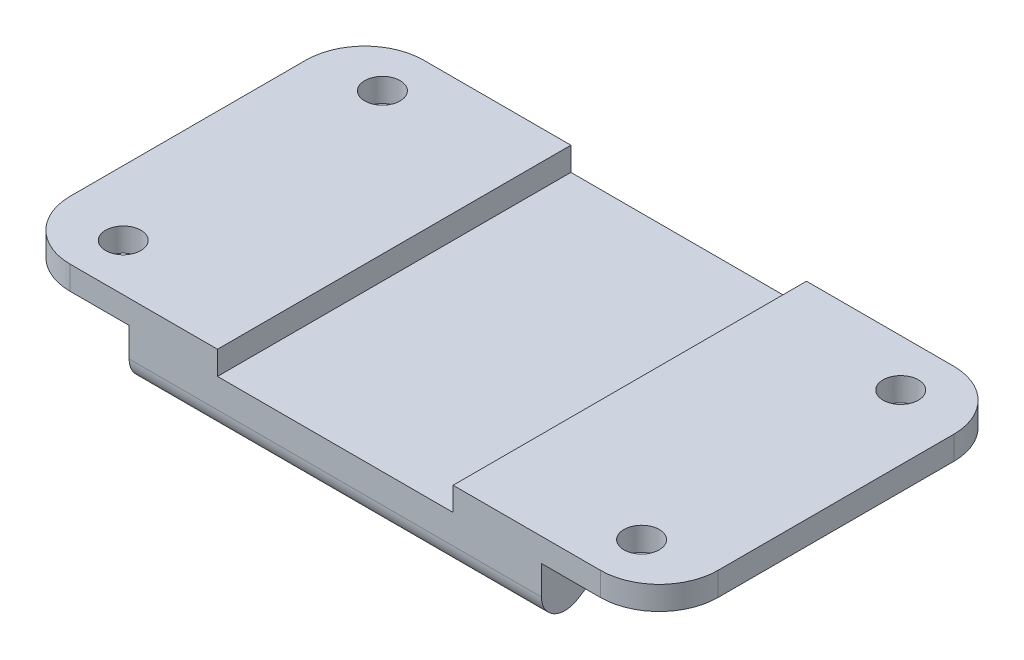
SolidWorks part; units mm, degrees
material "PEI"
ref_plane "Front Plane" through (0, 0, 0) normal (0, 0, 1) x (1, 0, 0)
ref_plane "Top Plane" through (0, 0, 0) normal (0, 1, 0) x (1, 0, 0)
ref_plane "Right Plane" through (0, 0, 0) normal (1, 0, 0) x (0, 0, -1)
sketch "Sketch1" plane through (0, 0, 0) normal (0, 1, 0) x (1, 0, 0)
  line L1 (17.5, -15) -> (-17.5, -15)
  line L2 (17.5, -15) -> (17.5, 15)
  line L3 (17.5, 15) -> (-17.5, 15)
  line L4 (-17.5, -15) -> (-17.5, 15)
  line L5 (17.5, -15) -> (-17.5, 15) construction
  line L6 (17.5, 15) -> (-17.5, -15) construction
  point P0 (0, 0)
  dimension "D1" = 30
  dimension "D2" = 35
extrude "Boss-Extrude1" add sketch "Sketch1" against normal blind 8
sketch "Sketch2" plane through (17.5, 0, 0) normal (1, 0, 0) x (0, 0, -1)
  line L0 (-15, -8) -> (-10, -5)
  line L1 (-10, -5) -> (10, -5)
  line L2 (0, -5) -> (0, -8)
  line L3 (15, -8) -> (10, -5)
  line L4 (15, 0) -> (-15, 0)
  line L5 (-15, 0) -> (-15, -8)
  line L6 (-15, -8) -> (15, -8)
  line L7 (15, -8) -> (15, 0)
  line L8 (15, 0) -> (-15, 0)
  line L9 (-15, 0) -> (-15, -8)
  line L10 (-15, -8) -> (15, -8)
  line L11 (15, -8) -> (15, 0)
  line M7 (-15, -8) -> (15, -8)
  dimension "D2" = 5
  dimension "D3" = 3
  dimension "D1" = 0
extrude "Cut-Extrude1" cut sketch "Sketch2" against normal through all and the other way through all contours L2 L1 L0 M7 | L3 L1 L2 M7
fillet "Fillet1" radius 2 4 edges at (0, -5, 10) (0, -5, -10) (0, -8, -15) (0, -8, 15)
sketch "Sketch3" plane through (0, 0, 15) normal (0, 0, 1) x (1, 0, 0)
  line L0 (-17.5, 0) -> (17.5, 0) construction
  line L1 (-10, 2) -> (10, 2)
  line L2 (-10, 2) -> (-10, -2)
  line L3 (-10, -2) -> (10, -2)
  line L4 (-17.5, 0) -> (-17.5, -4.4676)
  line L5 (-17.5, -4.4676) -> (17.5, -4.4676)
  line L6 (17.5, -4.4676) -> (17.5, 0)
  line L7 (17.5, 0) -> (-17.5, 0)
  line L8 (-17.5, 0) -> (-17.5, -4.4676)
  line L9 (-17.5, -4.4676) -> (17.5, -4.4676)
  line L10 (17.5, -4.4676) -> (17.5, 0)
  line L11 (17.5, 0) -> (-17.5, 0)
  line L12 (10, 2) -> (10, -2)
  line L13 (-10, 2) -> (10, -2) construction
  line L14 (-10, -2) -> (10, 2) construction
  line L15 (0, 0) -> (0, -4.4676)
  point P2 (0, 0)
  point P18 (0, 0)
  line M10 (17.5, 0) -> (-17.5, 0)
  dimension "D2" = 20
  dimension "D3" = 4
  dimension "D1" = 0
sketch "Sketch5" plane through (-17.5, 0, 0) normal (-1, 0, 0) x (0, 0, 1)
  line L1 (-15, 0) -> (15, 0)
  line L2 (-15, 0) -> (-15, -2)
  line L3 (-15, -2) -> (15, -2)
  line L4 (15, 0) -> (15, -2)
  line L6 (-15, 0) -> (-15, -4.4676)
  line L7 (-11.971, -6.1826) -> (-10.475, -5.285)
  line L8 (-9.446, -5) -> (9.446, -5)
  line L9 (10.475, -5.285) -> (11.971, -6.1826)
  line L10 (15, -4.4676) -> (15, 0)
  line L11 (15, 0) -> (-15, 0)
  line L12 (-15, 0) -> (-15, -4.4676)
  line L13 (-11.971, -6.1826) -> (-10.475, -5.285)
  line L14 (-9.446, -5) -> (9.446, -5)
  line L15 (10.475, -5.285) -> (11.971, -6.1826)
  line L16 (15, -4.4676) -> (15, 0)
  line L17 (15, 0) -> (-15, 0)
  arc A4 (-15, -4.4676) -> (-11.971, -6.1826) centre (-13, -4.4676) ccw
  arc A5 (-9.446, -5) -> (-10.475, -5.285) centre (-9.446, -7) ccw
  arc A6 (10.475, -5.285) -> (9.446, -5) centre (9.446, -7) ccw
  arc A7 (11.971, -6.1826) -> (15, -4.4676) centre (13, -4.4676) ccw
  arc A8 (-15, -4.4676) -> (-11.971, -6.1826) centre (-13, -4.4676) ccw
  arc A9 (-9.446, -5) -> (-10.475, -5.285) centre (-9.446, -7) ccw
  arc A10 (10.475, -5.285) -> (9.446, -5) centre (9.446, -7) ccw
  arc A11 (11.971, -6.1826) -> (15, -4.4676) centre (13, -4.4676) ccw
  line M13 (-15, 0) -> (-15, -4.4676)
  line M21 (15, -4.4676) -> (15, 0)
  line M22 (15, 0) -> (-15, 0)
  dimension "D2" = 2
  dimension "D1" = 0
extrude "Boss-Extrude2" add sketch "Sketch5" along normal blind 10 contours L3 M13 M21 M22
mirror "Mirror1" about plane through (0, 0, 0) normal (1, 0, 0) of "Boss-Extrude2"
sketch "Sketch6" plane through (0, 0, 0) normal (0, 1, 0) x (1, 0, 0)
  line L0 (0, 0) -> (-22, 0)
  line L1 (-22, 0) -> (-22, 11)
  line L2 (0, 0) -> (0, 15)
  line L4 (27.5, 15) -> (-27.5, 15)
  line L5 (-27.5, 15) -> (-27.5, -15)
  line L6 (-27.5, -15) -> (27.5, -15)
  line L7 (27.5, -15) -> (27.5, 15)
  line L8 (27.5, 15) -> (-27.5, 15)
  line L9 (-27.5, 15) -> (-27.5, -15)
  line L10 (-27.5, -15) -> (27.5, -15)
  line L11 (27.5, -15) -> (27.5, 15)
  circle A0 centre (-22, 11) radius 1.5
  circle A1 centre (-22, -11) radius 1.5
  circle A2 centre (22, -11) radius 1.5
  circle A3 centre (22, 11) radius 1.5
  dimension "D4" = 3
  dimension "D2" = 11
  dimension "D3" = 22
  dimension "D1" = 0
extrude "Cut-Extrude2" cut sketch "Sketch6" against normal blind 10
extrude "Cut-Extrude3" cut sketch "Sketch3" against normal through all contours L11 L15 L3 L12 | L15 L2 L3 M10
fillet "Fillet3" radius 5 4 edges at (27.5, -1, -15) (27.5, -1, 15) (-27.5, -1, -15) (-27.5, -1, 15)
